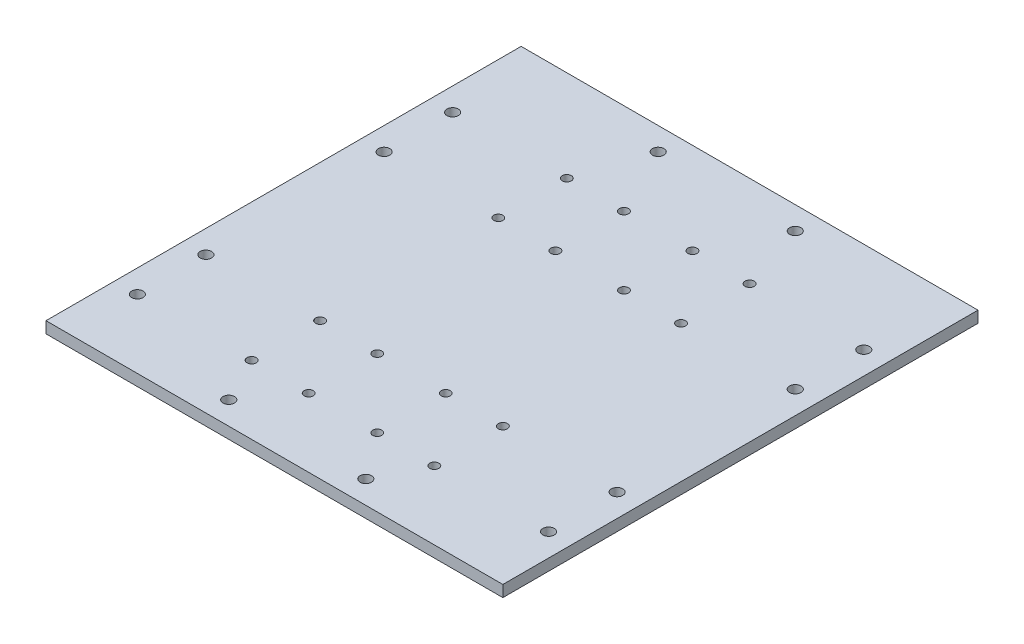
SolidWorks part; units mm, degrees
ref_plane "前视基准面" through (0, 0, 0) normal (0, 0, 1) x (1, 0, 0)
ref_plane "上视基准面" through (0, 0, 0) normal (0, 1, 0) x (1, 0, 0)
ref_plane "右视基准面" through (0, 0, 0) normal (1, 0, 0) x (0, 0, -1)
sketch "草图2" plane through (0, 0, 0) normal (0, 1, 0) x (1, 0, 0)
  line L1 (0, 0) -> (200, 0)
  line L2 (0, 0) -> (0, 208)
  line L3 (0, 208) -> (200, 208)
  line L4 (200, 0) -> (200, 208)
  dimension "D1" = 200
  dimension "D2" = 208
extrude "凸台-拉伸1" add sketch "草图2" along normal blind 5
hole_wizard "Ø4.0 (4) 直径孔1" positions "草图4" profile "草图3" hole size "Ø4.0" standard "GB" end condition through all
sketch "草图4" plane through (0, 5, 0) normal (0, 1, 0) x (1, 0, 0)
  line L0 (100, 208) -> (100, 0) construction
  line L1 (200, 208) -> (0, 208) construction
  line L2 (0, 0) -> (200, 0) construction
  line L3 (0, 208) -> (0, 0) construction
  point P0 (60, 168)
  point P2 (85, 168)
  point P4 (60, 138)
  point P5 (85, 138)
  point P7 (60, 60)
  point P9 (85, 60)
  point P11 (60, 30)
  point P13 (85, 30)
  point P36 (115, 30)
  point P37 (140, 30)
  point P38 (115, 60)
  point P39 (140, 60)
  point P40 (115, 138)
  point P41 (140, 138)
  point P42 (115, 168)
  point P43 (140, 168)
  dimension "D1" = 25
  dimension "D2" = 30
  dimension "D3" = 30
  dimension "D4" = 40
  dimension "D5" = 30
  dimension "D6" = 60
sketch "草图3" plane through (60, 5, -168) normal (1, 0, 0) x (0, 0, 1)
  line L0 (0, 0) -> (0, 5)
  line L1 (0, 5) -> (2, 5)
  line L2 (2, 5) -> (2, 0)
  line L5 (2, 0) -> (0, 0)
  line L11 (0, -6.35) -> (0, 107.95) construction
  dimension "通孔孔直径" = 4
  dimension "通孔孔深度" = 5
hole_wizard "Ø5.0 (5) 直径孔1" positions "草图6" profile "草图5" hole size "Ø5.0" standard "GB" end condition through all
sketch "草图6" plane through (0, 5, 0) normal (0, 1, 0) x (1, 0, 0)
  line L0 (200, 208) -> (0, 208) construction
  line L1 (0, 0) -> (200, 0) construction
  line L2 (0, 208) -> (0, 0) construction
  line L3 (100, 208) -> (100, 0) construction
  point P0 (10, 168)
  point P2 (10, 138)
  point P4 (10, 60)
  point P6 (10, 30)
  point P8 (70, 198)
  point P10 (70, 10)
  point P26 (130, 10)
  point P27 (130, 198)
  point P28 (190, 30)
  point P29 (190, 60)
  point P30 (190, 138)
  point P31 (190, 168)
  dimension "D1" = 30
  dimension "D2" = 30
  dimension "D3" = 40
  dimension "D4" = 30
  dimension "D5" = 70
  dimension "D6" = 10
  dimension "D7" = 10
  dimension "D8" = 10
sketch "草图5" plane through (10, 5, -168) normal (1, 0, 0) x (0, 0, 1)
  line L0 (0, 0) -> (0, 5)
  line L1 (0, 5) -> (2.5, 5)
  line L2 (2.5, 5) -> (2.5, 0)
  line L5 (2.5, 0) -> (0, 0)
  line L11 (0, -6.35) -> (0, 107.95) construction
  dimension "通孔孔直径" = 5
  dimension "通孔孔深度" = 5
